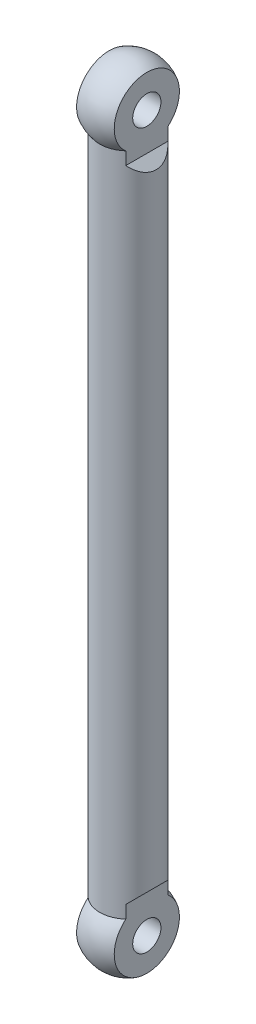
SolidWorks part; units mm, degrees
ref_plane "前视基准面" through (0, 0, 0) normal (0, 0, 1) x (1, 0, 0)
ref_plane "上视基准面" through (0, 0, 0) normal (0, 1, 0) x (1, 0, 0)
ref_plane "右视基准面" through (0, 0, 0) normal (1, 0, 0) x (0, 0, -1)
sketch "草图1" plane through (0, 0, 0) normal (1, 0, 0) x (0, 0, -1)
  line L0 (0, 0) -> (0, 76) construction
  line L1 (3, 2.6458) -> (3, 73.3542)
  line L2 (0, 76) -> (0, 86.2776) construction
  line L3 (0, 0) -> (0, -9.9252) construction
  line L4 (0, -4) -> (0, 80)
  arc A0 (0, -4) -> (3, 2.6458) centre (0, 0) ccw
  arc A1 (3, 73.3542) -> (0, 80) centre (0, 76) ccw
  dimension "D2" = 8
  dimension "D3" = 8
  dimension "D1" = 76
  dimension "D4" = 6
revolve "旋转1" add sketch "草图1" angle 360 about L4
sketch "草图2" plane through (0, 0, 0) normal (0, 0, 1) x (1, 0, 0)
  line L0 (0, 0) -> (0, 76) construction
  line L1 (2, 81) -> (2, 72)
  line L2 (2, 72) -> (3, 71)
  line L3 (3, 2.6458) -> (3, 73.3542) construction
  line L4 (3, 71) -> (8, 71)
  line L5 (8, 71) -> (8, 81)
  line L6 (8, 81) -> (2, 81)
  line L7 (0, 38) -> (25.6817, 38) construction
  line L8 (8, -5) -> (2, -5)
  line L9 (8, 5) -> (8, -5)
  line L10 (3, 5) -> (8, 5)
  line L11 (2, 4) -> (3, 5)
  line L12 (2, -5) -> (2, 4)
  arc A0 (3, 73.3542) -> (-3, 73.3542) centre (0, 76) ccw construction
  dimension "D1" = 2
  dimension "D2" = 45
  dimension "D3" = 34
  dimension "D4" = 10
  dimension "D5" = 5
extrude "切除-拉伸1" cut sketch "草图2" against normal through all both and the other way through all
mirror "镜向1" about plane through (0, 0, 0) normal (1, 0, 0) of "切除-拉伸1"
sketch "草图3" plane through (2, 0, 0) normal (1, 0, 0) x (0, 0, -1)
  circle A0 centre (0, 76) radius 1.5
  circle A1 centre (0, 0) radius 1.5
  arc A2 (2.2361, 73.3542) -> (-2.2361, 73.3542) centre (0, 76) ccw construction
  dimension "D1" = 3
extrude "切除-拉伸2" cut sketch "草图3" against normal through all
move or copy body "实体-移动/复制1" [suppressed] bodies to move or copy 109
move or copy body "实体-移动/复制2" [suppressed] bodies to move or copy 110 parameters "D1"=0, "D2"=0, "D3"=0
move or copy body "实体-移动/复制3" [suppressed] bodies to move or copy 111 parameters "D1"=0, "D2"=0, "D3"=0
